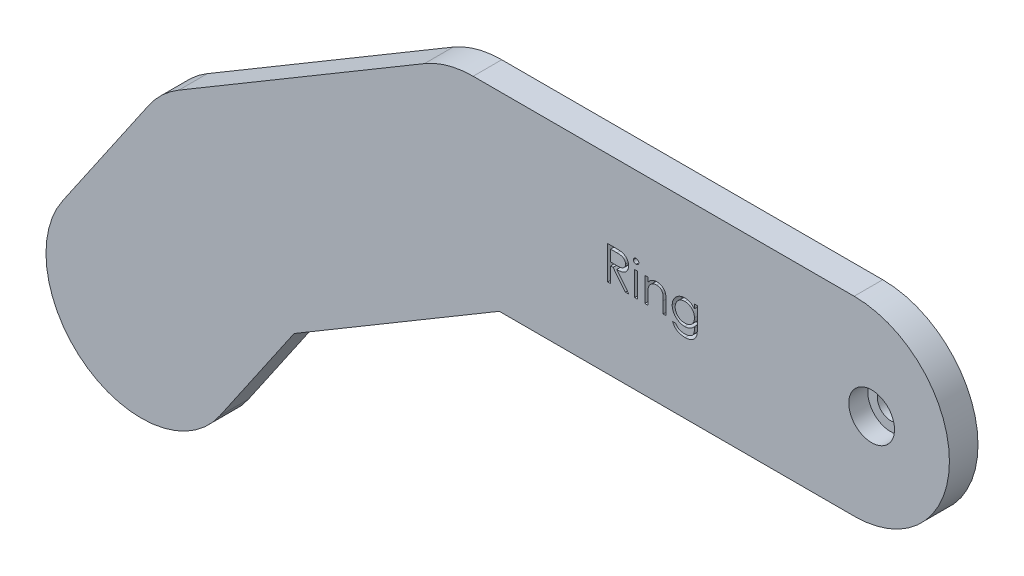
SolidWorks part; units mm, degrees
ref_plane "Front Plane" through (0, 0, 0) normal (0, 0, 1) x (1, 0, 0)
ref_plane "Top Plane" through (0, 0, 0) normal (0, 1, 0) x (1, 0, 0)
ref_plane "Right Plane" through (0, 0, 0) normal (1, 0, 0) x (0, 0, -1)
sketch "Sketch1" plane through (0, 0, 0) normal (0, 0, 1) x (1, 0, 0)
  line L0 (0, 0) -> (40, 0) construction
  line L2 (0, 10) -> (40, 10)
  line L3 (0, -10) -> (40, -10)
  arc A0 (0, 10) -> (0, -10) centre (0, 0) ccw
  arc A1 (40, -10) -> (40, 10) centre (40, 0) ccw
  point P5 (20, 0)
extrude "Boss-Extrude1" add sketch "Sketch1" along normal blind 3
sketch "Sketch2" plane through (0, 0, 0) normal (0, 0, 1) x (1, 0, 0)
  line L0 (0, 0) -> (-25.7976, -15.3128) construction
  line L2 (5.1043, -8.5992) -> (-20.6934, -23.912)
  line L3 (-5.1043, 8.5992) -> (-30.9019, -6.7136)
  arc A0 (5.1043, -8.5992) -> (-5.1043, 8.5992) centre (0, 0) ccw
  arc A1 (-30.9019, -6.7136) -> (-20.6934, -23.912) centre (-25.7976, -15.3128) ccw
  point P5 (-12.8988, -7.6564)
extrude "Boss-Extrude2" add sketch "Sketch2" along normal blind 3
sketch "Sketch3" plane through (0, 0, 0) normal (0, 0, 1) x (1, 0, 0)
  line L0 (-25.7976, -15.3128) -> (-34.8419, -28.5113) construction
  line L2 (-17.5486, -20.9655) -> (-26.5928, -34.164)
  line L3 (-34.0467, -9.6601) -> (-43.091, -22.8586)
  arc A0 (-17.5486, -20.9655) -> (-34.0467, -9.6601) centre (-25.7976, -15.3128) ccw
  arc A1 (-43.091, -22.8586) -> (-26.5928, -34.164) centre (-34.8419, -28.5113) ccw
  point P5 (-30.3198, -21.912)
extrude "Boss-Extrude4" add sketch "Sketch3" along normal blind 3
sketch "Sketch4" plane through (0, 0, 0) normal (0, 0, 1) x (1, 0, 0)
  circle A0 centre (41.8354, 0) radius 1.4
extrude "Cut-Extrude5" cut sketch "Sketch4" along normal blind 3
sketch "Sketch5" plane through (0, 0, 3) normal (0, 0, 1) x (1, 0, 0)
  circle A0 centre (41.8354, 0) radius 2.4
extrude "Cut-Extrude6" cut sketch "Sketch5" against normal blind 2
sketch "Sketch7" plane through (0, 0, 3) normal (0, 0, 1) x (1, 0, 0)
  text T0 "Ring"
extrude "Cut-Extrude7" cut sketch "Sketch7" against normal blind 1
